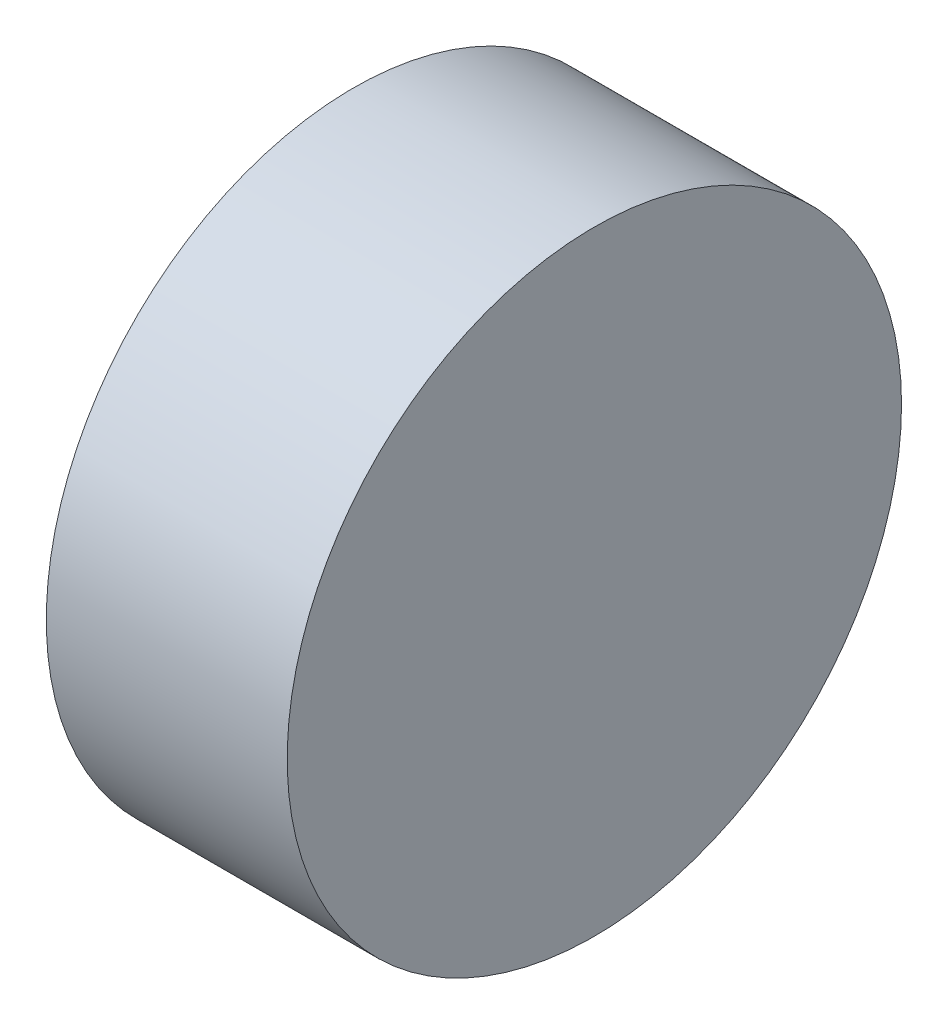
SolidWorks part; units mm, degrees
ref_plane "前视基准面" through (0, 0, 0) normal (0, 0, 1) x (1, 0, 0)
ref_plane "上视基准面" through (0, 0, 0) normal (0, 1, 0) x (1, 0, 0)
ref_plane "右视基准面" through (0, 0, 0) normal (1, 0, 0) x (0, 0, -1)
sketch "草图1" plane through (0, 0, 0) normal (1, 0, 0) x (0, 0, -1)
  circle A0 centre (0, 0) radius 51
  dimension "D1" = 102
extrude "凸台-拉伸1" add sketch "草图1" along normal blind 40
sketch "草图2" plane through (0, 0, 0) normal (-1, 0, 0) x (0, 0, 1)
  circle A0 centre (0, 0) radius 23
  dimension "D1" = 46
extrude "凸台-拉伸2" add sketch "草图2" along normal blind 10
